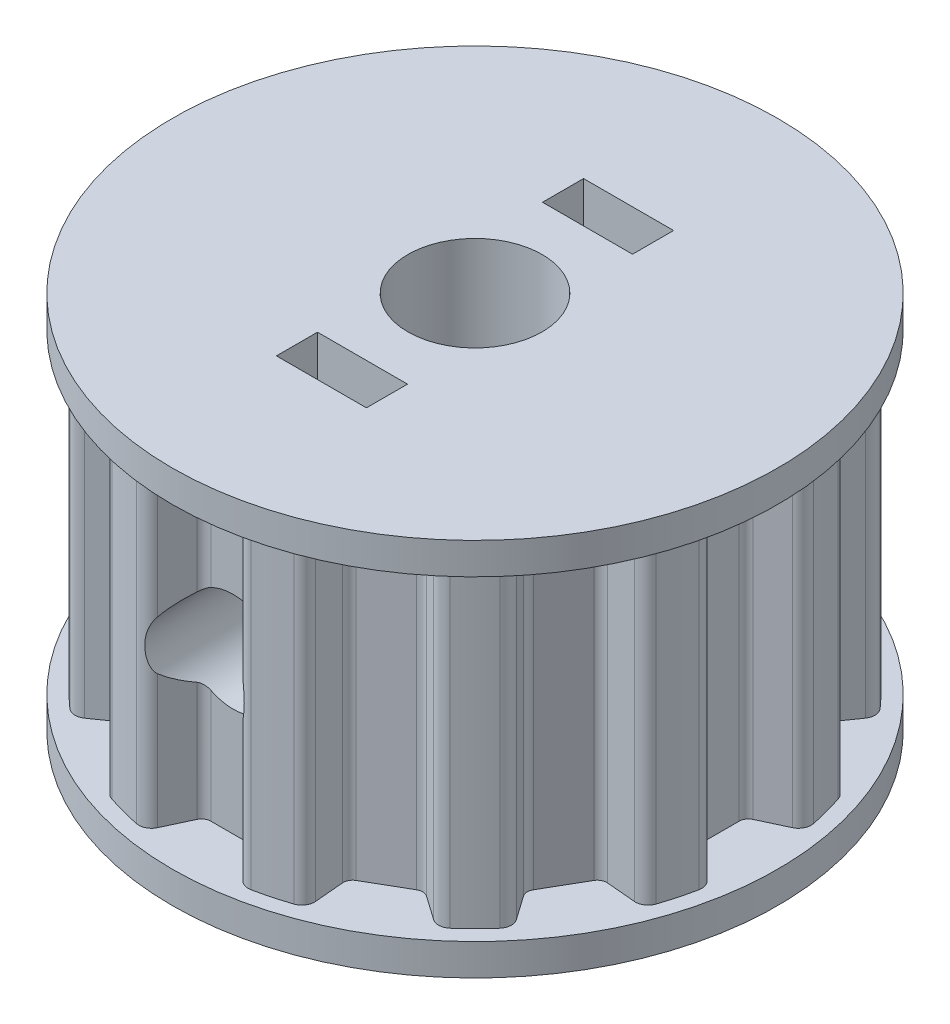
SolidWorks part; units mm, degrees
ref_plane "Front Plane" through (0, 0, 0) normal (0, 0, 1) x (1, 0, 0)
ref_plane "Top Plane" through (0, 0, 0) normal (0, 1, 0) x (1, 0, 0)
ref_plane "Right Plane" through (0, 0, 0) normal (1, 0, 0) x (0, 0, -1)
sketch "Sketch1" plane through (0, 0, 0) normal (0, 1, 0) x (1, 0, 0)
  circle A0 centre (0, 0) radius 18.175
  dimension "D1" = 36.35
extrude "Boss-Extrude1" add sketch "Sketch1" along normal blind 20
sketch "Sketch2" plane through (0, 20, 0) normal (0, 1, 0) x (1, 0, 0)
  line L0 (0, 0) -> (0, 18.175) construction
  line L1 (-3, 17.9257) -> (3, 17.9257) construction
  line L2 (1.7855, 15.3211) -> (-1.7855, 15.3211)
  line L3 (-1.7855, 15.3211) -> (-3, 17.9257)
  line L4 (1.7855, 15.3211) -> (3, 17.9257)
  circle A0 centre (0, 0) radius 18.175 construction
  point P11 (0, 15.3211)
  dimension "D1" = 6
  dimension "D2" = 25
  dimension "D3" = 2.8539
extrude "Cut-Extrude1" cut sketch "Sketch2" against normal blind 20 and the other way through all
pattern_circular "CirPattern4" count 12 over 360 about axis through (0, 20, 0) along (0, 1, 0) of "Cut-Extrude1"
fillet "Fillet2" radius 0.8 24 edges at (3, 10, -17.9257) (-3, 10, -17.9257) (6.3648, 10, -17.0241) (11.5609, 10, -14.0241) (14.0241, 10, -11.5609) (17.0241, 10, -6.3648) (17.9257, 10, -3) (17.9257, 10, 3) (17.0241, 10, 6.3648) (14.0241, 10, 11.5609) (11.5609, 10, 14.0241) (6.3648, 10, 17.0241) (3, 10, 17.9257) (-3, 10, 17.9257) (-6.3648, 10, 17.0241) (-11.5609, 10, 14.0241) (-14.0241, 10, 11.5609) (-17.0241, 10, 6.3648) (-17.9257, 10, 3) (-17.9257, 10, -3) (-17.0241, 10, -6.3648) (-14.0241, 10, -11.5609) (-11.5609, 10, -14.0241) (-6.3648, 10, -17.0241)
fillet "Fillet1" radius 0.6 24 edges at (1.7855, 10, -15.3211) (-1.7855, 10, -15.3211) (6.1143, 10, -14.1612) (9.2068, 10, -12.3757) (12.3757, 10, -9.2068) (14.1612, 10, -6.1143) (15.3211, 10, -1.7855) (15.3211, 10, 1.7855) (14.1612, 10, 6.1143) (12.3757, 10, 9.2068) (9.2068, 10, 12.3757) (6.1143, 10, 14.1612) (1.7855, 10, 15.3211) (-1.7855, 10, 15.3211) (-6.1143, 10, 14.1612) (-9.2068, 10, 12.3757) (-12.3757, 10, 9.2068) (-14.1612, 10, 6.1143) (-15.3211, 10, 1.7855) (-15.3211, 10, -1.7855) (-14.1612, 10, -6.1143) (-12.3757, 10, -9.2068) (-6.1143, 10, -14.1612) (-9.2068, 10, -12.3757)
sketch "Sketch3" plane through (0, 0, 0) normal (0, -1, 0) x (1, 0, 0)
  circle A0 centre (0, 0) radius 19.175
  dimension "D1" = 38.35
extrude "Boss-Extrude2" add sketch "Sketch3" along normal blind 2
sketch "Sketch4" plane through (0, 20, 0) normal (0, 1, 0) x (1, 0, 0)
  circle A0 centre (0, 0) radius 19.175
  circle A1 centre (0, 0) radius 19.175 construction
extrude "Boss-Extrude3" add sketch "Sketch4" along normal blind 2
sketch "Sketch5" plane through (0, 22, 0) normal (0, 1, 0) x (1, 0, 0)
  circle A0 centre (0, 0) radius 4.25
  dimension "D1" = 8.5
extrude "Cut-Extrude2" cut sketch "Sketch5" against normal through all both and the other way through all
sketch "Sketch6" plane through (0, 22, 0) normal (0, 1, 0) x (1, 0, 0)
  line L0 (0, 19.175) -> (0, -19.175) construction
  line L1 (-19.175, 0) -> (19.175, 0) construction
  line L2 (-2.85, -9.725) -> (2.85, -9.725)
  line L3 (-2.85, 7.125) -> (2.85, 7.125)
  line L4 (-2.85, 7.125) -> (-2.85, 9.725)
  line L5 (-2.85, 9.725) -> (2.85, 9.725)
  line L6 (2.85, 7.125) -> (2.85, 9.725)
  line L7 (-2.85, 7.125) -> (2.85, 9.725) construction
  line L8 (-2.85, 9.725) -> (2.85, 7.125) construction
  line L9 (2.85, -7.125) -> (2.85, -9.725)
  line L10 (-2.85, -7.125) -> (2.85, -7.125)
  line L11 (-2.85, -7.125) -> (-2.85, -9.725)
  circle A0 centre (0, 0) radius 19.175 construction
  point P7 (0, 8.425)
  dimension "D1" = 5.7
  dimension "D2" = 2.6
  dimension "D3" = 7.125
extrude "Cut-Extrude3" cut sketch "Sketch6" against normal through all both
sketch "Sketch7" plane through (0, 0, -15.3211) normal (0, 0, -1) x (-1, 0, 0)
  line L0 (0, 0) -> (0, 20) construction
  line L1 (1.4032, 20) -> (-1.4032, 20) construction
  circle A0 centre (0, 10) radius 1.5
  dimension "D1" = 3
extrude "Cut-Extrude4" cut sketch "Sketch7" against normal through all both
sketch "Sketch8" plane through (0, 0, -15.3211) normal (0, 0, -1) x (-1, 0, 0)
  circle A0 centre (0, 10) radius 3.15
  dimension "D1" = 6.3
extrude "Cut-Extrude5" cut sketch "Sketch8" against normal blind 4.5 and the other way blind 4
sketch "Sketch9" plane through (0, 0, 15.3211) normal (0, 0, 1) x (1, 0, 0)
  circle A0 centre (0, 10) radius 3.15
  dimension "D1" = 6.3
extrude "Cut-Extrude6" cut sketch "Sketch9" against normal blind 4.5 and the other way blind 4
